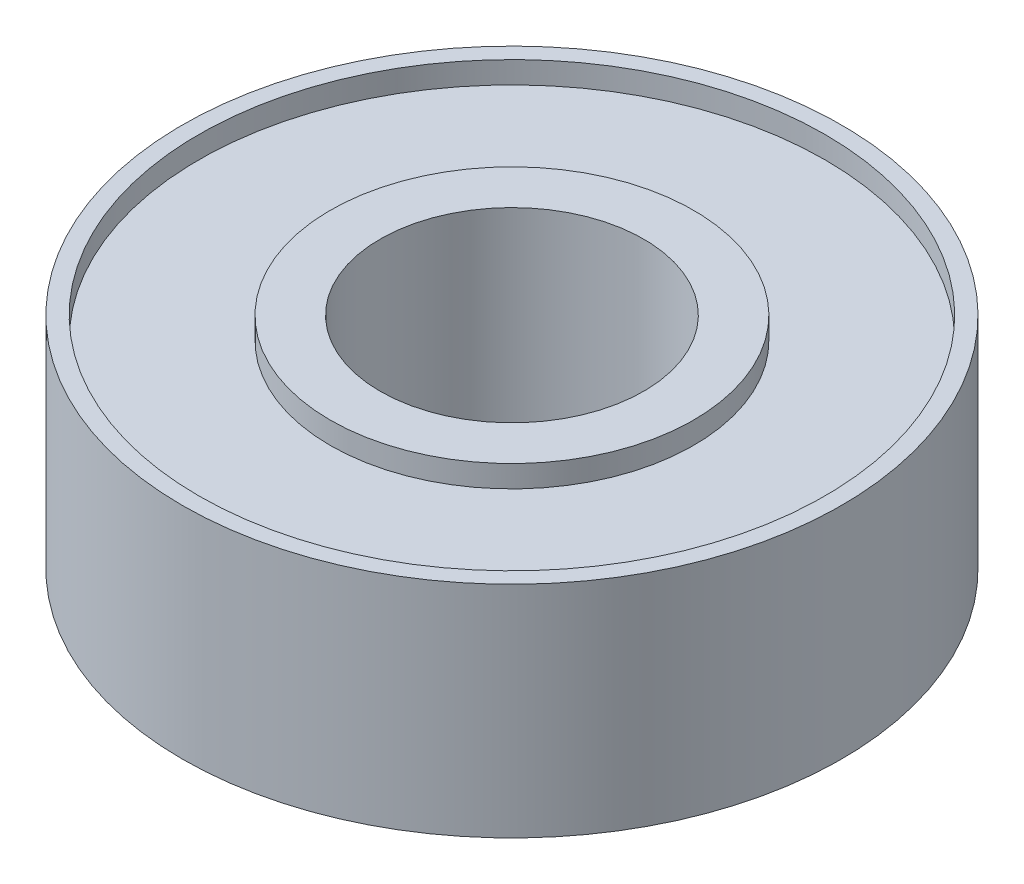
SolidWorks part; units mm, degrees
material "Acero aleado"
ref_plane "Alzado" through (0, 0, 0) normal (0, 0, 1) x (1, 0, 0)
ref_plane "Planta" through (0, 0, 0) normal (0, 1, 0) x (1, 0, 0)
ref_plane "Vista lateral" through (0, 0, 0) normal (1, 0, 0) x (0, 0, -1)
sketch "Croquis1" plane through (0, 0, 0) normal (0, 1, 0) x (1, 0, 0)
  circle A0 centre (0, 0) radius 3
  circle A1 centre (0, 0) radius 7.5
  dimension "D1" = 15
  dimension "D2" = 6
extrude "Saliente-Extruir1" add sketch "Croquis1" along normal blind 5
sketch "Croquis2" plane through (0, 5, 0) normal (0, 1, 0) x (1, 0, 0)
  circle A0 centre (0, 0) radius 4.1352
  circle A1 centre (0, 0) radius 7.1249
extrude "Cortar-Extruir1" cut sketch "Croquis2" against normal blind 0.5
sketch "Croquis3" plane through (0, 0, 0) normal (0, -1, 0) x (1, 0, 0)
  circle A0 centre (0, 0) radius 3.5416
  circle A1 centre (0, 0) radius 6.927
extrude "Cortar-Extruir2" cut sketch "Croquis3" against normal blind 0.5
